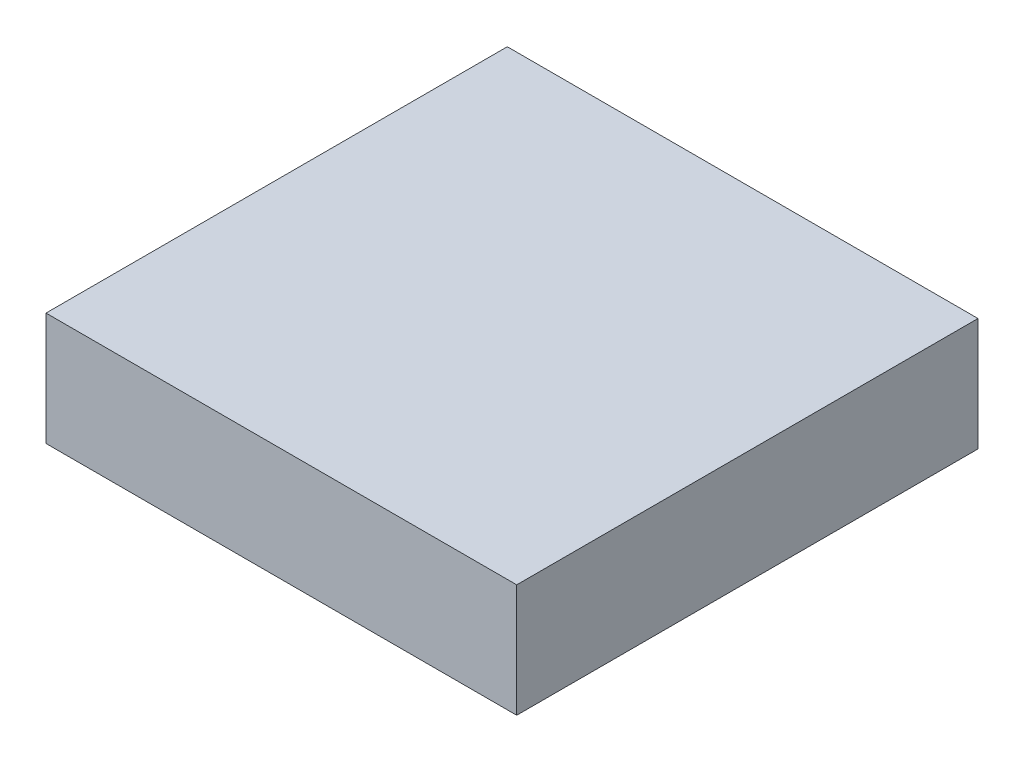
SolidWorks part; units mm, degrees
ref_plane "Alzado" through (0, 0, 0) normal (0, 0, 1) x (1, 0, 0)
ref_plane "Planta" through (0, 0, 0) normal (0, 1, 0) x (1, 0, 0)
ref_plane "Vista lateral" through (0, 0, 0) normal (1, 0, 0) x (0, 0, -1)
sketch "Croquis1" plane through (734.1906, -662.1331, 235.4239) normal (0, 1, 0) x (1, 0, 0)
  line L0 (11.9021, -49.9174) -> (111.9021, -49.9174)
  line L1 (11.9021, -49.9174) -> (11.9021, 48.0826)
  line L2 (111.9021, -49.9174) -> (111.9021, 48.0826)
  line L3 (11.9021, 48.0826) -> (111.9021, 48.0826)
  line L4 (11.9021, -49.9174) -> (111.9021, 48.0826) construction
  line L5 (111.9021, -49.9174) -> (11.9021, 48.0826) construction
  point P1 (61.9021, -0.9174)
  dimension "D1" = 100
  dimension "D2" = 98
extrude "Saliente-Extruir1" add sketch "Croquis1" along normal blind 24
